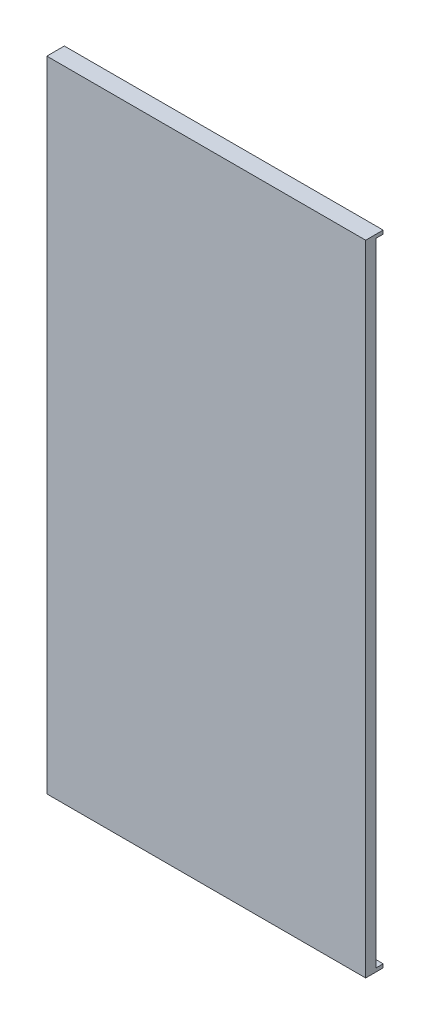
SolidWorks part; units mm, degrees
ref_plane "Płaszczyzna przednia" through (0, 0, 0) normal (0, 0, 1) x (1, 0, 0)
ref_plane "Płaszczyzna górna" through (0, 0, 0) normal (0, 1, 0) x (1, 0, 0)
ref_plane "Płaszczyzna prawa" through (0, 0, 0) normal (1, 0, 0) x (0, 0, -1)
sketch "Szkic1" plane through (0, 0, 0) normal (0, 0, 1) x (1, 0, 0)
  line L1 (0, 0) -> (224.5, 0)
  line L2 (0, 0) -> (0, 449.9)
  line L3 (0, 449.9) -> (224.5, 449.9)
  line L4 (224.5, 0) -> (224.5, 449.9)
  dimension "D1" = 449.9
  dimension "D2" = 224.5
extrude "Dodanie-wyciągnięcie1" add sketch "Szkic1" along normal blind 12.33
sketch "Szkic2" plane through (0, 0, 0) normal (0, 0, -1) x (-1, 0, 0)
  line L8 (-2.5, 2.5) -> (-2.5, 447.4)
  line L9 (-2.5, 447.4) -> (-222, 447.4)
  line L10 (-222, 447.4) -> (-222, 2.5)
  line L11 (-222, 2.5) -> (-2.5, 2.5)
  line L12 (-2.5, 2.5) -> (-2.5, 447.4)
  line L13 (-2.5, 447.4) -> (-222, 447.4)
  line L14 (-222, 447.4) -> (-222, 2.5)
  line L15 (-222, 2.5) -> (-2.5, 2.5)
  dimension "D1" = 2.5
extrude "Wytnij-wyciągnięcie1" cut sketch "Szkic2" against normal blind 10
sketch "Szkic3" plane through (0, 0, 0) normal (0, 0, -1) x (-1, 0, 0)
  line L1 (-2.5, 2.5) -> (0, 2.5)
  line L2 (-2.5, 2.5) -> (-2.5, 449.9)
  line L3 (-2.5, 449.9) -> (0, 449.9)
  line L4 (0, 2.5) -> (0, 449.9)
  point P6 (0, 450)
sketch "Szkic4" plane through (0, 0, 0) normal (0, 0, -1) x (-1, 0, 0)
  line L0 (-224.5, 0) -> (-224.5, 449.9) construction
  line L1 (-222, 2.5) -> (-224.5, 2.5)
  line L2 (-222, 2.5) -> (-222, 447.4)
  line L3 (-222, 447.4) -> (-224.5, 447.4)
  line L4 (-224.5, 2.5) -> (-224.5, 447.4)
  dimension "D1" = 0
extrude "Wytnij-wyciągnięcie3" cut sketch "Szkic4" against normal blind 5
